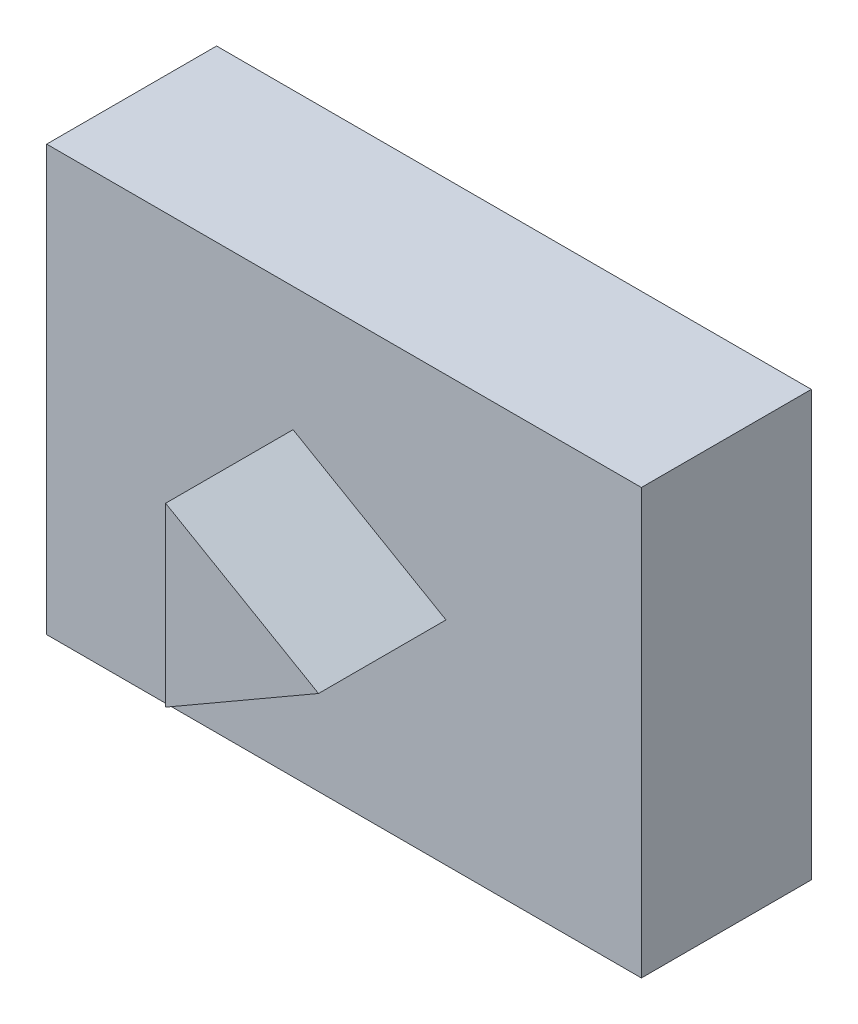
SolidWorks part; units mm, degrees
ref_plane "前视基准面" through (0, 0, 0) normal (0, 0, 1) x (1, 0, 0)
ref_plane "上视基准面" through (0, 0, 0) normal (0, 1, 0) x (1, 0, 0)
ref_plane "右视基准面" through (0, 0, 0) normal (1, 0, 0) x (0, 0, -1)
sketch "草图1" plane through (0, 0, 0) normal (0, 0, 1) x (1, 0, 0)
  line L1 (-35, 25) -> (35, 25)
  line L2 (-35, 25) -> (-35, -25)
  line L3 (-35, -25) -> (35, -25)
  line L4 (35, 25) -> (35, -25)
  line L5 (-35, 25) -> (35, -25) construction
  line L6 (-35, -25) -> (35, 25) construction
  point P0 (0, 0)
  point P5 (0, 0)
  dimension "D1" = 50
  dimension "D2" = 70
extrude "凸台-拉伸1" add sketch "草图1" along normal mid plane 20
sketch "草图2" plane through (0, 0, 10) normal (0, 0, 1) x (1, 0, 0)
  line L1 (12, 0) -> (-6, 10.3923)
  line L2 (-6, 10.3923) -> (-6, -10.3923)
  line L3 (-6, -10.3923) -> (12, 0)
  circle A0 centre (0, 0) radius 6 construction
  point P1 (-6, 10.3923)
extrude "凸台-拉伸2" add sketch "草图2" along normal blind 15
